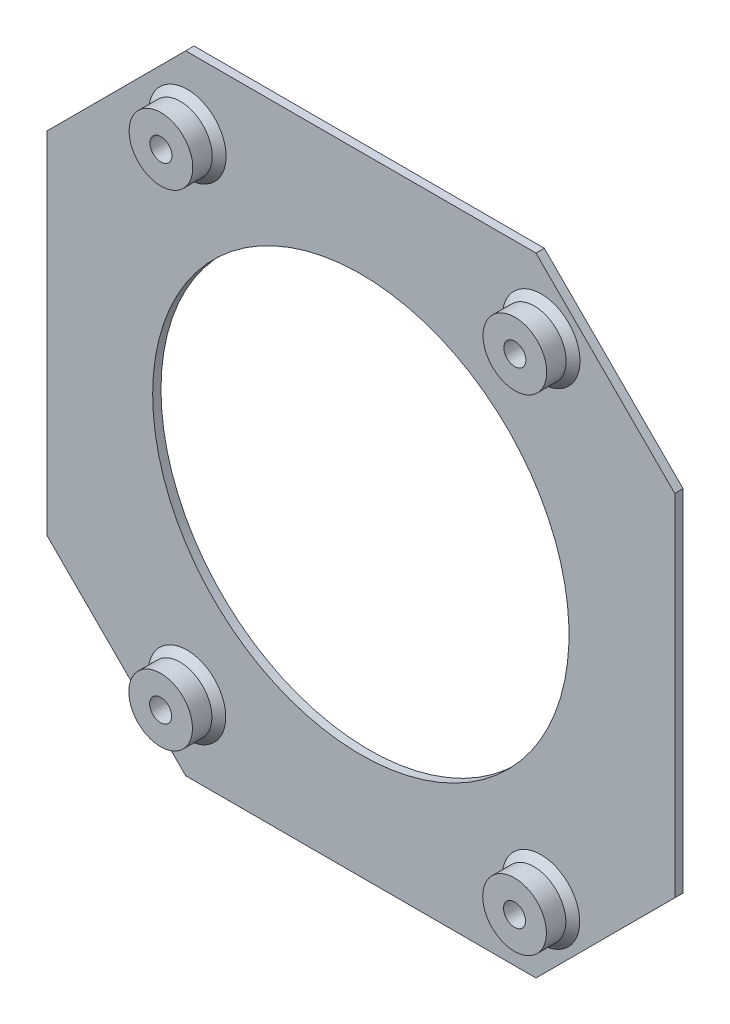
SolidWorks part; units mm, degrees
ref_plane "Front Plane" through (0, 0, 0) normal (0, 0, 1) x (1, 0, 0)
ref_plane "Top Plane" through (0, 0, 0) normal (0, 1, 0) x (1, 0, 0)
ref_plane "Right Plane" through (0, 0, 0) normal (1, 0, 0) x (0, 0, -1)
sketch "Sketch2" plane through (0, 4.7625, 0) normal (0, 1, 0) x (1, 0, 0)
  line L0 (-45.2375, 0) -> (-45.2375, -10.475) construction
  line L1 (45.2375, 0) -> (-45.2375, 0)
  line L2 (45.2375, 0) -> (45.2375, -1.2)
  line L3 (45.2375, -1.2) -> (-45.2375, -1.2)
  line L4 (-45.2375, 0) -> (-45.2375, -1.2)
  dimension "D1" = 1.2
extrude "Boss-Extrude1" add sketch "Sketch2" along normal up to vertex (90.475 mm away)
sketch "Sketch3" plane through (0, 0, 5) normal (0, 0, -1) x (-1, 0, 0)
  circle A0 centre (25.0039, 84.9602) radius 1.5875 construction
  circle A1 centre (-25.996, 84.927) radius 1.5875 construction
  circle A2 centre (25.0039, 84.9602) radius 1.5875
  circle A3 centre (-25.996, 84.927) radius 1.5875
  circle A4 centre (25.0495, 14.9604) radius 1.5875 construction
  circle A5 centre (-25.9504, 14.9271) radius 1.5875 construction
  circle A6 centre (25.0495, 14.9604) radius 1.5875
  circle A7 centre (-25.9504, 14.9271) radius 1.5875
extrude "Extrude-Thin1" add sketch "Sketch3" along normal up to surface (3.8 mm away) thin
chamfer "Chamfer1" distance 1 angle 45 4 edges at (21.3629, 14.9271, 1.2) (-29.637, 14.9604, 1.2) (-29.5914, 84.9602, 1.2) (21.4085, 84.927, 1.2)
sketch "Sketch5" plane through (0, 0, 0) normal (0, 0, -1) x (-1, 0, 0)
  line L0 (0, 95.2375) -> (0, 4.7625) construction
  line L1 (-45.2375, 95.2375) -> (45.2375, 95.2375) construction
  line L2 (-45.2375, 4.7625) -> (45.2375, 4.7625) construction
  circle A0 centre (0, 50) radius 30
  dimension "D1" = 60
extrude "Cut-Extrude1" cut sketch "Sketch5" against normal through all
chamfer "Chamfer2" distance 20 angle 45 4 edges at (45.2375, 4.7625, 0.6) (-45.2375, 4.7625, 0.6) (-45.2375, 95.2375, 0.6) (45.2375, 95.2375, 0.6)
